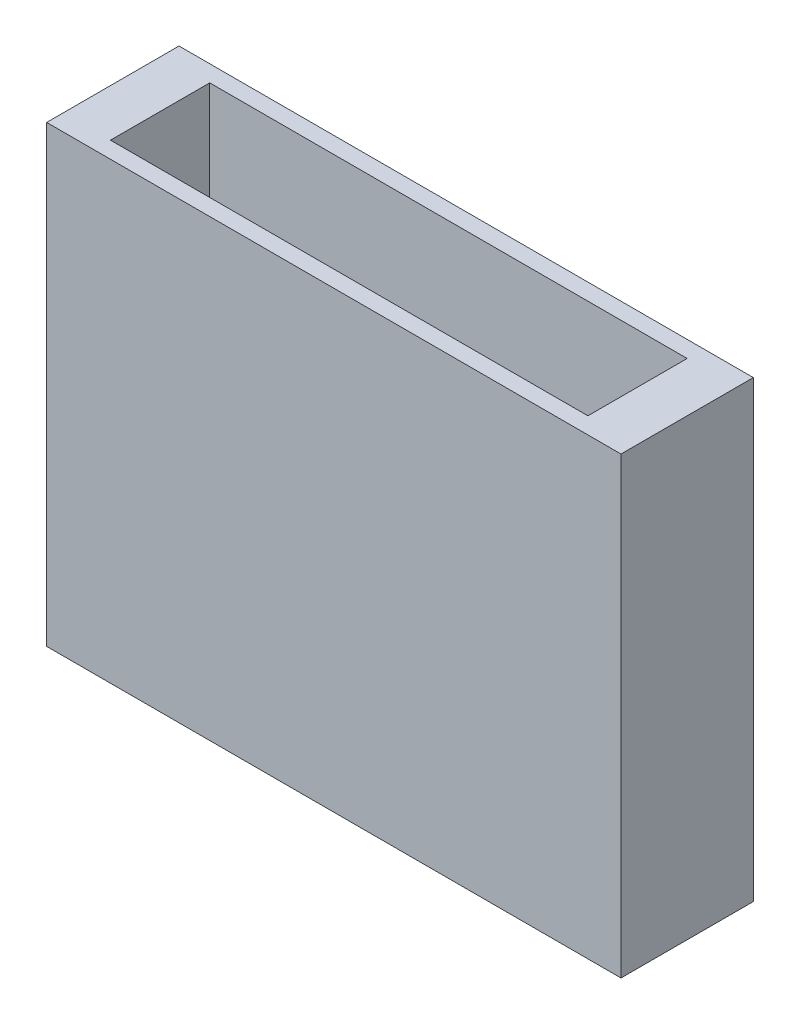
SolidWorks part; units mm, degrees
ref_plane "Alzado" through (0, 0, 0) normal (0, 0, 1) x (1, 0, 0)
ref_plane "Planta" through (0, 0, 0) normal (0, 1, 0) x (1, 0, 0)
ref_plane "Vista lateral" through (0, 0, 0) normal (1, 0, 0) x (0, 0, -1)
sketch "Croquis1" plane through (0, 0, 0) normal (0, 0, 1) x (1, 0, 0)
  line L1 (0, 0) -> (24.3, 0)
  line L2 (0, 0) -> (0, 19.2)
  line L3 (0, 19.2) -> (24.3, 19.2)
  line L4 (24.3, 0) -> (24.3, 19.2)
  dimension "D1" = 24.3
  dimension "D2" = 19.2
extrude "Saliente-Extruir1" add sketch "Croquis1" along normal blind 5.6
sketch "Croquis2" plane through (0, 19.2, 0) normal (0, 1, 0) x (1, 0, 0)
  line L0 (0, -5.6) -> (0, 0) construction
  line L1 (2, -4.9) -> (22.2, -4.9)
  line L2 (2, -4.9) -> (2, -0.7)
  line L3 (2, -0.7) -> (22.2, -0.7)
  line L4 (22.2, -4.9) -> (22.2, -0.7)
  line L5 (24.3, -5.6) -> (0, -5.6) construction
  point P6 (0, -2.8)
  dimension "D1" = 20.2
  dimension "D2" = 2
  dimension "D3" = 4.2
  dimension "D4" = 0.7
extrude "Cortar-Extruir1" cut sketch "Croquis2" against normal blind 18
sketch "Croquis3" plane through (0, 0, 0) normal (0, 0, -1) x (-1, 0, 0)
  line L2 (-24.3, 0) -> (-24.3, 19.2) construction
  line L3 (-14.65, 6.8) -> (-9.65, 6.8)
  line L4 (-14.65, 6.8) -> (-14.65, 13)
  line L5 (-14.65, 13) -> (-9.65, 13)
  line L6 (-9.65, 6.8) -> (-9.65, 13)
  line L7 (0, 0) -> (-24.3, 0) construction
  dimension "D1" = 9.65
  dimension "D2" = 6.8
  dimension "D3" = 5
  dimension "D4" = 6.2
extrude "Cortar-Extruir2" cut sketch "Croquis3" against normal blind 2
sketch "Croquis5" plane through (0, 0, 0) normal (0, 0, -1) x (-1, 0, 0)
  line L1 (-14.65, 13) -> (-9.65, 13)
  line L2 (-14.65, 13) -> (-14.65, 6.8)
  line L3 (-14.65, 6.8) -> (-9.65, 6.8)
  line L4 (-9.65, 13) -> (-9.65, 6.8)
  line L5 (-21.0425, 16.8401) -> (-3.0425, 16.8401)
  line L6 (-21.0425, 16.8401) -> (-21.0425, 2.8401)
  line L7 (-21.0425, 2.8401) -> (-3.0425, 2.8401)
  line L8 (-3.0425, 16.8401) -> (-3.0425, 2.8401)
  dimension "D1" = 18
  dimension "D2" = 14
extrude "Saliente-Extruir3" add sketch "Croquis5" along normal blind 2
fillet "Redondeo1" radius 1 8 edges at (9.65, 9.9, -2) (12.15, 13, -2) (14.65, 9.9, -2) (12.15, 6.8, -2) (12.0425, 16.8401, -2) (3.0425, 9.8401, -2) (12.0425, 2.8401, -2) (21.0425, 9.8401, -2)
